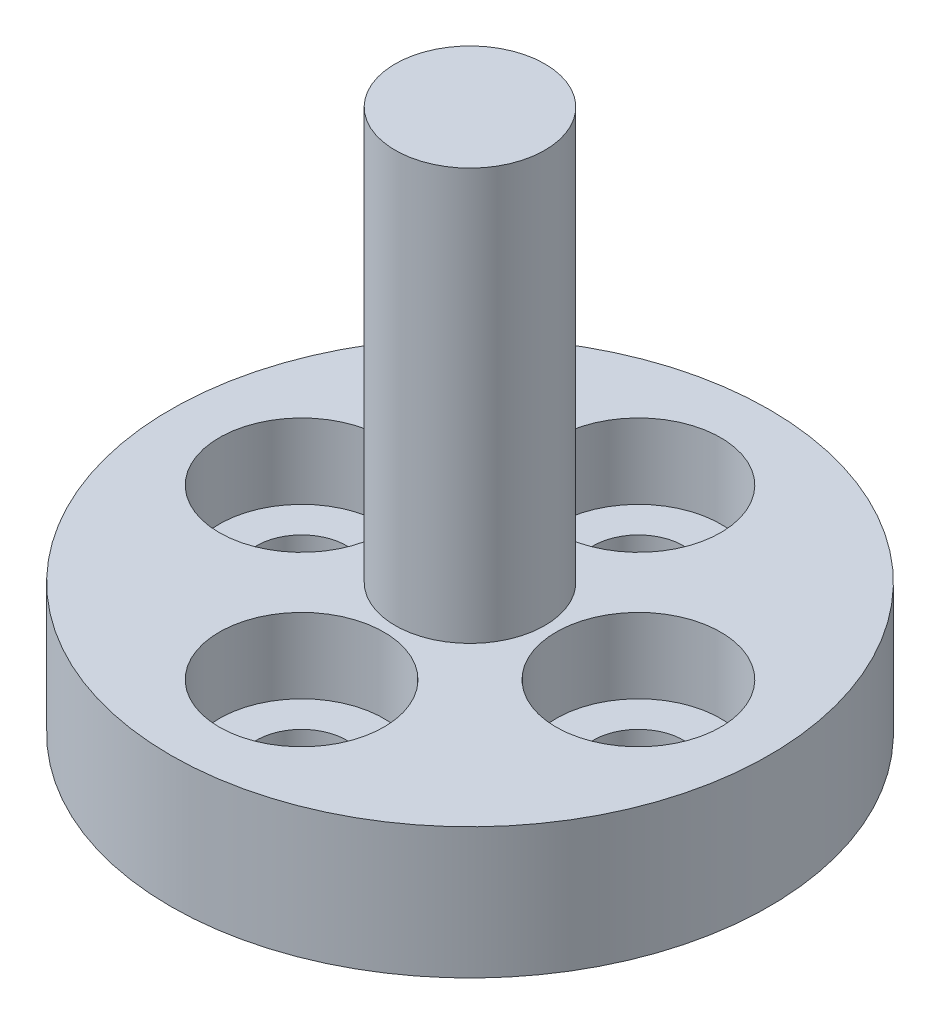
SolidWorks part; units mm, degrees
ref_plane "Front Plane" through (0, 0, 0) normal (0, 0, 1) x (1, 0, 0)
ref_plane "Top Plane" through (0, 0, 0) normal (0, 1, 0) x (1, 0, 0)
ref_plane "Right Plane" through (0, 0, 0) normal (1, 0, 0) x (0, 0, -1)
sketch "Sketch1" plane through (0, 0, 0) normal (0, 0, 1) x (1, 0, 0)
  line L0 (0, 0) -> (0, 14.5)
  line L1 (0, 14.5) -> (2, 14.5)
  line L2 (2, 14.5) -> (2, 3.5)
  line L3 (2, 3.5) -> (8, 3.5)
  line L4 (8, 3.5) -> (8, 0)
  line L5 (8, 0) -> (0, 0)
  dimension "D1" = 14.5
  dimension "D2" = 2
  dimension "D3" = 11
  dimension "D4" = 8
revolve "Revolve1" add sketch "Sketch1" angle 360 about L0
sketch "Sketch3" plane through (0, 3.5, 0) normal (0, 1, 0) x (1, 0, 0)
  circle A0 centre (0, 0) radius 4.5
  dimension "D1" = 9
sketch "Sketch4" plane through (0, 3.5, 0) normal (0, 1, 0) x (1, 0, 0)
  line L0 (0, 8) -> (0, -8) construction
  line L1 (-8, 0) -> (8, 0) construction
  circle A0 centre (0, 0) radius 8 construction
sketch "Sketch5" plane through (0, 3.5, 0) normal (0, 1, 0) x (1, 0, 0)
  line L1 (-8, 0) -> (8, 0) construction
  line L3 (0, 8) -> (0, -8) construction
  circle A0 centre (0, 0) radius 4.5 construction
  point P0 (0, 4.5)
  point P1 (4.5, 0)
  point P2 (0, 0)
  point P3 (-4.5, 0)
  point P4 (0, -4.5)
  point P5 (-10.3533, 0.2194)
  point P6 (0, 0)
  point P7 (0, 0)
  point P11 (0, 0)
  point P13 (0, 0)
  point P14 (0, 0)
  point P17 (0, 0)
  point P18 (0, 0)
  point P19 (0, 0)
  point P20 (0, 0)
  point P21 (0, 0)
  point P22 (0, 0)
  point P23 (0, 0)
  point P24 (0, 0)
  point P25 (0, 0)
hole_wizard "CBORE for M2 Socket Head Cap Screw1" positions "3DSketch1" profile "Sketch6" counterbore size "M2" standard "IS"
sketch3d "3DSketch1"
  point P0 (0, 3.5, 4.5)
  point P3 (4.5, 3.5, 0)
  point P6 (0, 3.5, -4.5)
  point P9 (-4.5, 3.5, 0)
sketch "Sketch6" plane through (0, 3.5, 4.5) normal (1, 0, 0) x (0, 0, 1)
  line L0 (0, 0) -> (0, 11)
  line L1 (0, 11) -> (1.2, 10.279)
  line L2 (1.2, 10.279) -> (1.2, 2)
  line L3 (1.2, 2) -> (2.2, 2)
  line L4 (2.2, 2) -> (2.2, 0)
  line L5 (2.2, 0) -> (0, 0)
  line L10 (0, 11) -> (-1.2, 10.279) construction
  line L11 (0, -6.35) -> (0, 107.95) construction
  dimension "Hole Dia." = 2.4
  dimension "Hole Depth" = 11
  dimension "C'Bore Dia." = 4.4
  dimension "C'Bore Depth" = 2
  dimension "Drill Angle" = 118
